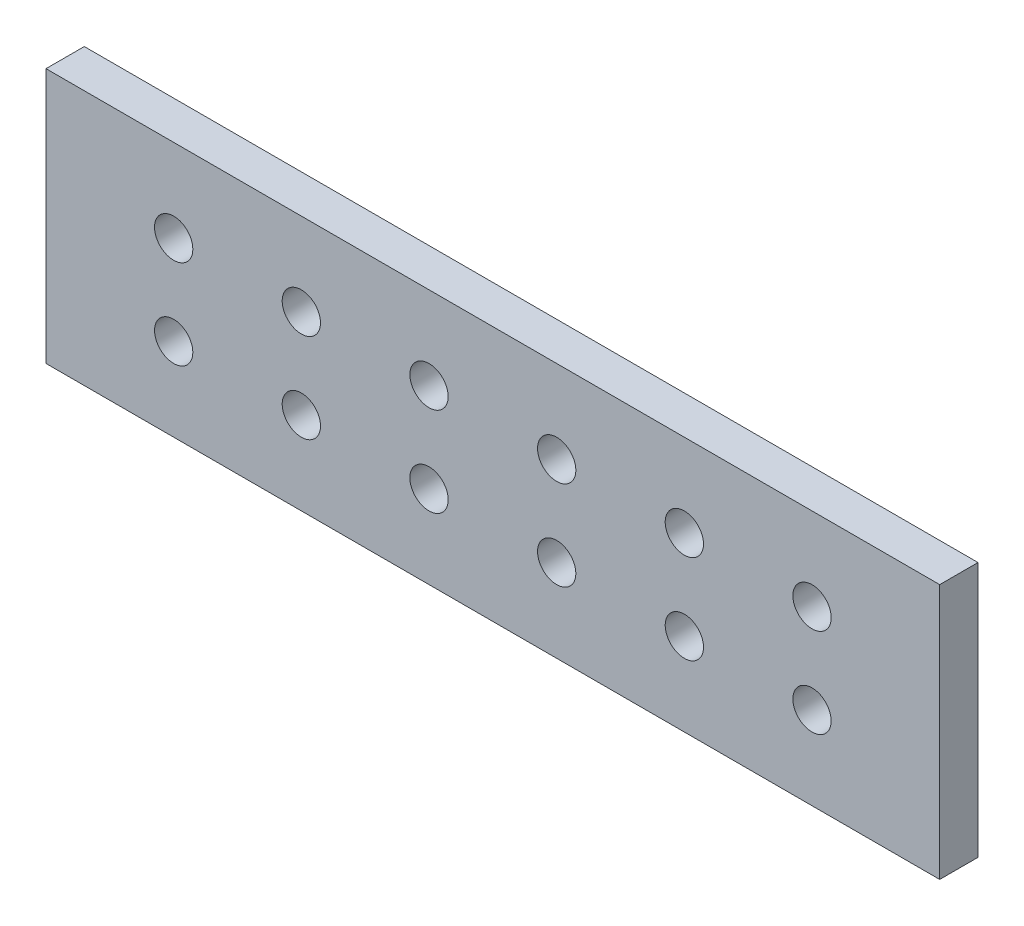
SolidWorks part; units mm, degrees
material "Maple"
ref_plane "Front Plane" through (0, 0, 0) normal (0, 0, 1) x (1, 0, 0)
ref_plane "Top Plane" through (0, 0, 0) normal (0, 1, 0) x (1, 0, 0)
ref_plane "Right Plane" through (0, 0, 0) normal (1, 0, 0) x (0, 0, -1)
sketch "Sketch1" plane through (0, 0, 0) normal (0, 0, 1) x (1, 0, 0)
  line L0 (-35, 0) -> (35, 0) construction
  line L1 (-35, 10) -> (35, 10)
  line L2 (-35, 10) -> (-35, -10)
  line L3 (-35, -10) -> (35, -10)
  line L4 (35, 10) -> (35, -10)
  line L5 (-35, 10) -> (35, -10) construction
  line L6 (-35, -10) -> (35, 10) construction
  line L7 (-25, 3.5) -> (-15, 3.5) construction
  line L8 (-15, 3.5) -> (-5, 3.5) construction
  line L9 (-5, 3.5) -> (5, 3.5) construction
  line L10 (5, 3.5) -> (15, 3.5) construction
  line L11 (15, 3.5) -> (25, 3.5) construction
  line L12 (25, 3.5) -> (25, 10) construction
  line L13 (25, -3.5) -> (25, -10) construction
  line L14 (-25, -3.5) -> (-15, -3.5) construction
  line L15 (-15, -3.5) -> (-5, -3.5) construction
  line L16 (-5, -3.5) -> (5, -3.5) construction
  line L17 (5, -3.5) -> (15, -3.5) construction
  line L18 (15, -3.5) -> (25, -3.5) construction
  circle A0 centre (-25, 3.5) radius 1.5
  circle A1 centre (-25, -3.5) radius 1.5
  circle A2 centre (-15, 3.5) radius 1.5
  circle A3 centre (-5, 3.5) radius 1.5
  circle A4 centre (5, 3.5) radius 1.5
  circle A5 centre (15, 3.5) radius 1.5
  circle A6 centre (25, 3.5) radius 1.5
  circle A9 centre (-15, -3.5) radius 1.5
  circle A10 centre (-5, -3.5) radius 1.5
  circle A11 centre (5, -3.5) radius 1.5
  circle A12 centre (15, -3.5) radius 1.5
  circle A13 centre (25, -3.5) radius 1.5
  point P0 (0, 0)
  dimension "D5" = 3
  dimension "D1" = 70
  dimension "D2" = 20
  dimension "D3" = 7
  dimension "D6" = 10
  dimension "D7" = 10
  dimension "D8" = 10
extrude "Boss-Extrude1" add sketch "Sketch1" along normal blind 3
